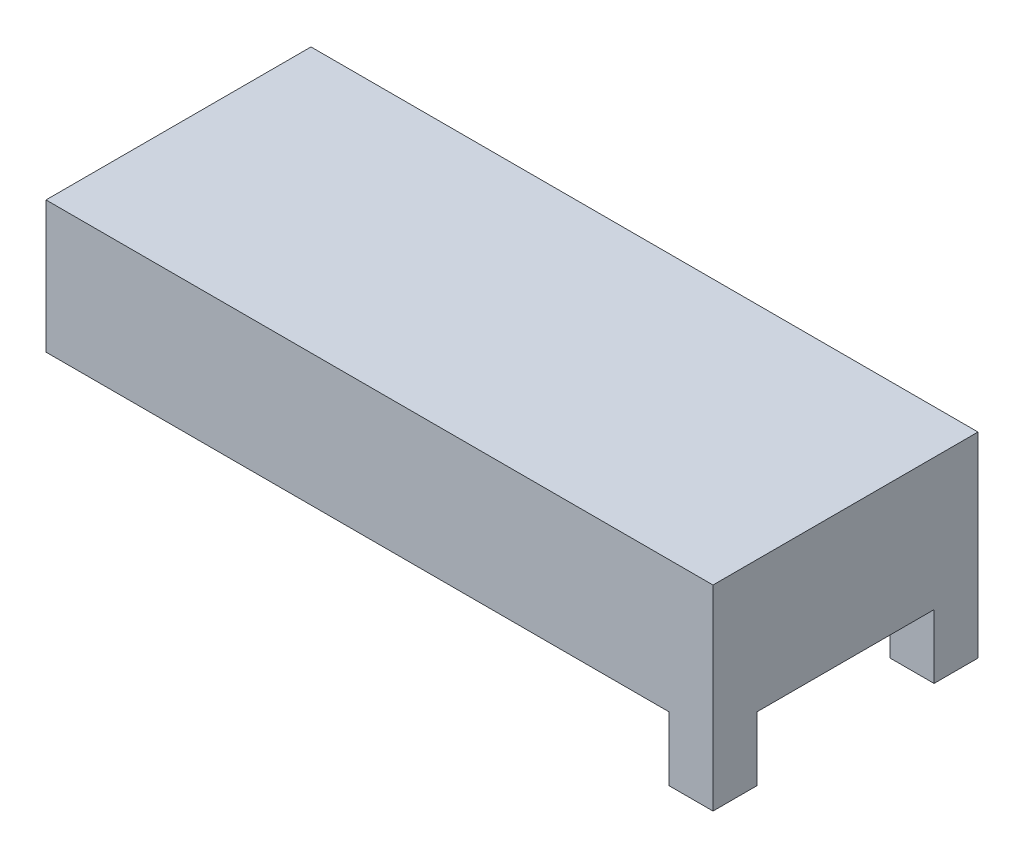
SolidWorks part; units mm, degrees
ref_plane "Front Plane" through (0, 0, 0) normal (0, 0, 1) x (1, 0, 0)
ref_plane "Top Plane" through (0, 0, 0) normal (0, 1, 0) x (1, 0, 0)
ref_plane "Right Plane" through (0, 0, 0) normal (1, 0, 0) x (0, 0, -1)
sketch "Sketch1" plane through (0, 0, 0) normal (0, 1, 0) x (1, 0, 0)
  line L1 (-28.355, -12.06) -> (28.355, -12.06)
  line L2 (-28.355, -12.06) -> (-28.355, 12.06)
  line L3 (-28.355, 12.06) -> (28.355, 12.06)
  line L4 (28.355, -12.06) -> (28.355, 12.06)
  line L5 (-28.355, -12.06) -> (28.355, 12.06) construction
  line L6 (-28.355, 12.06) -> (28.355, -12.06) construction
  point P0 (0, 0)
  dimension "D1" = 56.71
  dimension "D2" = 24.12
extrude "Boss-Extrude1" add sketch "Sketch1" along normal blind 12
sketch "Sketch3" plane through (28.355, 0, 0) normal (1, 0, 0) x (0, 0, -1)
  line L0 (-12.06, 12) -> (-12.06, -5.8216)
  line L1 (-12.06, -5.8216) -> (-8.06, -5.8216)
  line L2 (-8.06, -5.8216) -> (-8.06, 0)
  line L3 (-12.06, 0) -> (12.06, 0) construction
  line L4 (-8.06, 0) -> (8.06, 0)
  line L5 (8.06, 0) -> (8.06, -5.8216)
  line L6 (8.06, -5.8216) -> (12.06, -5.8216)
  line L7 (12.06, -5.8216) -> (12.06, 12)
  line L8 (12.06, 12) -> (-12.06, 12)
  dimension "D1" = 4
  dimension "D2" = 5.8216
extrude "Boss-Extrude3" add sketch "Sketch3" along normal blind 4
